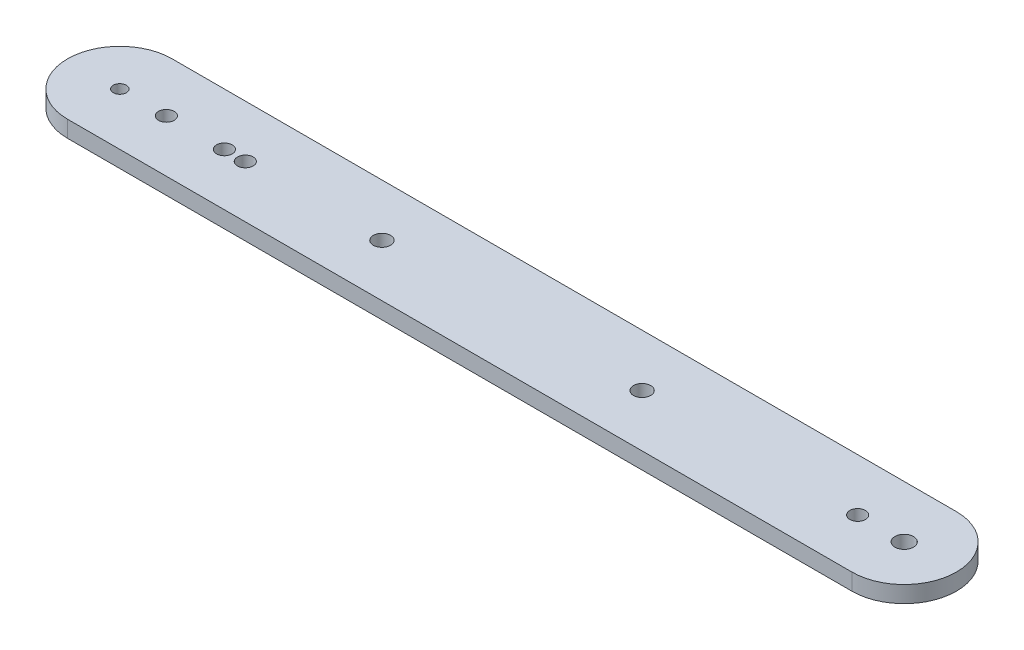
SolidWorks part; units mm, degrees
ref_plane "Front Plane" through (0, 0, 0) normal (0, 0, 1) x (1, 0, 0)
ref_plane "Top Plane" through (0, 0, 0) normal (0, 1, 0) x (1, 0, 0)
ref_plane "Right Plane" through (0, 0, 0) normal (1, 0, 0) x (0, 0, -1)
sketch "Sketch1" plane through (0, 0, 0) normal (0, 1, 0) x (1, 0, 0)
  line L0 (-85, -2.5) -> (85, -2.5) construction
  line L1 (-75, 7.5) -> (75, 7.5)
  line L3 (-75, -12.5) -> (75, -12.5)
  line L7 (0, 7.5) -> (0, -12.5) construction
  arc A0 (-75, 7.5) -> (-75, -12.5) centre (-75, -2.5) ccw
  arc A1 (75, -12.5) -> (75, 7.5) centre (75, -2.5) ccw
  circle A7 centre (-66.1, -2.5) radius 1.5
  circle A8 centre (-55, -2.5) radius 1.5
  circle A10 centre (-51, -2.5) radius 1.5
  circle A11 centre (66.1, -2.5) radius 1.5
  circle A12 centre (75, -2.5) radius 1.7758
  circle A13 centre (24.8747, -2.5) radius 1.65
  circle A14 centre (-24.8747, -2.5) radius 1.65
  circle A15 centre (-75, -2.5) radius 1.25
  point P0 (0, 0)
  dimension "D6" = 3
  dimension "D9" = 3.3
  dimension "D7" = 2.5
  dimension "D14" = 3
  dimension "D2" = 11.1
  dimension "D3" = 4
  dimension "D4" = 20
  dimension "D5" = 150
  dimension "D8" = 8.9
  dimension "D10" = 25
  dimension "D11" = 8.9
  dimension "D12" = 0
  dimension "D13" = 0
extrude "Boss-Extrude1" add sketch "Sketch1" along normal blind 3.175
